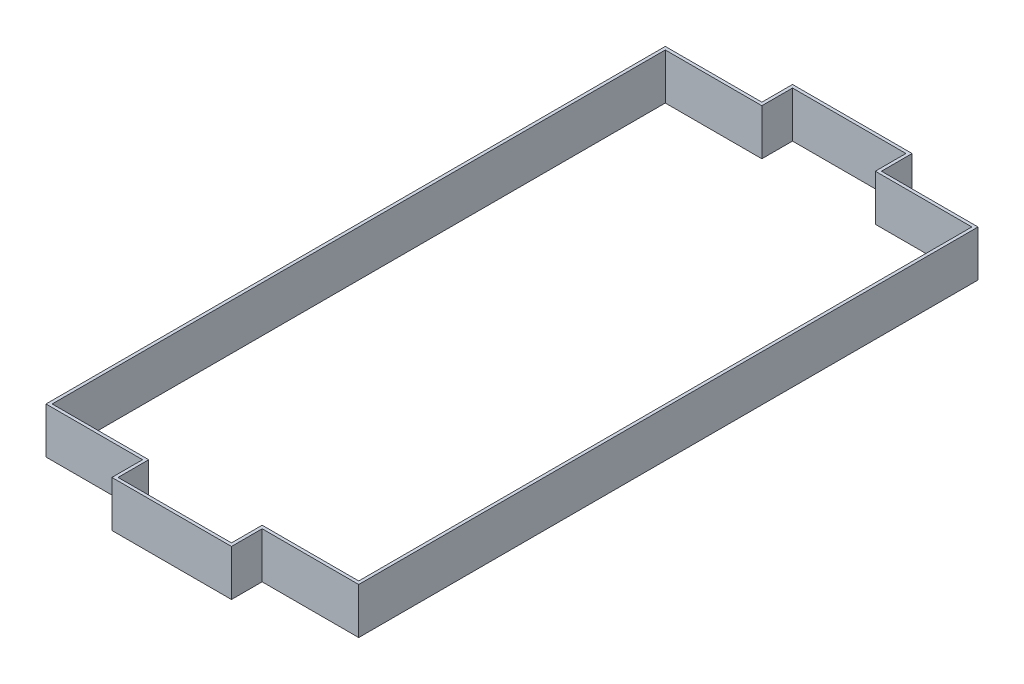
SolidWorks part; units mm, degrees
ref_plane "Front Plane" through (0, 0, 0) normal (0, 0, 1) x (1, 0, 0)
ref_plane "Top Plane" through (0, 0, 0) normal (0, 1, 0) x (1, 0, 0)
ref_plane "Right Plane" through (0, 0, 0) normal (1, 0, 0) x (0, 0, -1)
sketch "Sketch2" plane through (0, 0, 0) normal (0, 1, 0) x (1, 0, 0)
  line L2 (0, 0) -> (0, 2000)
  line L3 (0, 2000) -> (325, 2000)
  line L4 (1000, 0) -> (1000, 2000)
  line L8 (0, 990) -> (1000, 990)
  line L9 (0, 0) -> (325, 0)
  line L15 (325, 200) -> (675, 200)
  line L17 (0, 1010) -> (1000, 1010)
  line L31 (325, 200) -> (325, 0)
  line L32 (675, 200) -> (675, 0)
  line L33 (325, 2000) -> (325, 1800)
  line L34 (325, 1800) -> (675, 1800)
  line L35 (675, 1800) -> (675, 2000)
  line L36 (305, 2000) -> (305, 1780)
  line L37 (305, 1780) -> (695, 1780)
  line L38 (695, 1780) -> (695, 2000)
  line L39 (305, 220) -> (305, 0)
  line L40 (305, 220) -> (695, 220)
  line L41 (695, 220) -> (695, 0)
  line L44 (325, 0) -> (305, 0)
  line L45 (305, 0) -> (315, 0)
  line L46 (315, 0) -> (315, -100)
  line L47 (695, 0) -> (675, 0)
  line L48 (685, 0) -> (685, -100)
  line L49 (685, -100) -> (315, -100)
  line L50 (325, 2000) -> (305, 2000)
  line L51 (305, 2000) -> (315, 2000)
  line L52 (315, 2010) -> (315, 2100)
  line L53 (315, 2100) -> (685, 2100)
  line L54 (685, 2100) -> (685, 2000)
  line L55 (305, 2010) -> (305, 2010)
  line L56 (305, 2010) -> (305, 2110)
  line L57 (305, 2110) -> (695, 2110)
  line L58 (695, 2110) -> (695, 2010)
  line L60 (1010, -10) -> (1010, 2010)
  line L61 (-10, -10) -> (315, -10)
  line L62 (-10, -10) -> (-10, 2010)
  line L63 (305, -10) -> (305, -110)
  line L64 (695, -110) -> (305, -110)
  line L65 (695, -10) -> (695, -110)
  line L66 (685, 2010) -> (1010, 2010)
  line L67 (675, 2000) -> (1000, 2000)
  line L68 (-10, 2010) -> (1010, 2010) construction
  line L69 (315, 2010) -> (315, 2000)
  line L70 (0, 2000) -> (1000, 2000) construction
  line L71 (315, 2000) -> (315, 2100) construction
  line L72 (695, 2110) -> (695, 2000) construction
  line L73 (-10, 2010) -> (305, 2010)
  line L74 (305, 2010) -> (315, 2010)
  line L75 (325, 2000) -> (675, 2000)
  line L76 (675, 2000) -> (675, 1980.047)
  line L77 (675, 1980.047) -> (325, 1980.047)
  line L78 (325, 1980.047) -> (325, 2000)
  line L79 (685, -10) -> (1010, -10)
  line L80 (325, 20) -> (675, 20)
  line L81 (675, 0) -> (1000, 0)
  line L82 (-10, -10) -> (1010, -10) construction
  line L83 (325, 0) -> (675, 0)
  line L84 (0, 0) -> (1000, 0) construction
  line L86 (305, 0) -> (305, -110) construction
  line L87 (695, 0) -> (695, -110) construction
  circle A1 centre (500, 1000) radius 190
  circle A2 centre (500, 1000) radius 210
  point P27 (776.3821, -10)
  point P28 (224.454, -10)
extrude "Boss-Extrude1" add sketch "Sketch2" along normal blind 150 contours L79 L48 L49 L46 L61 L63 L64 L65 | L74 L73 L62 L61 L46 L9 L2 L3 L69 | L81 L47 L48 L79 L60 L66 L54 L67 L4 | L56 L74 L52 L53 L54 L66 L58 L57
